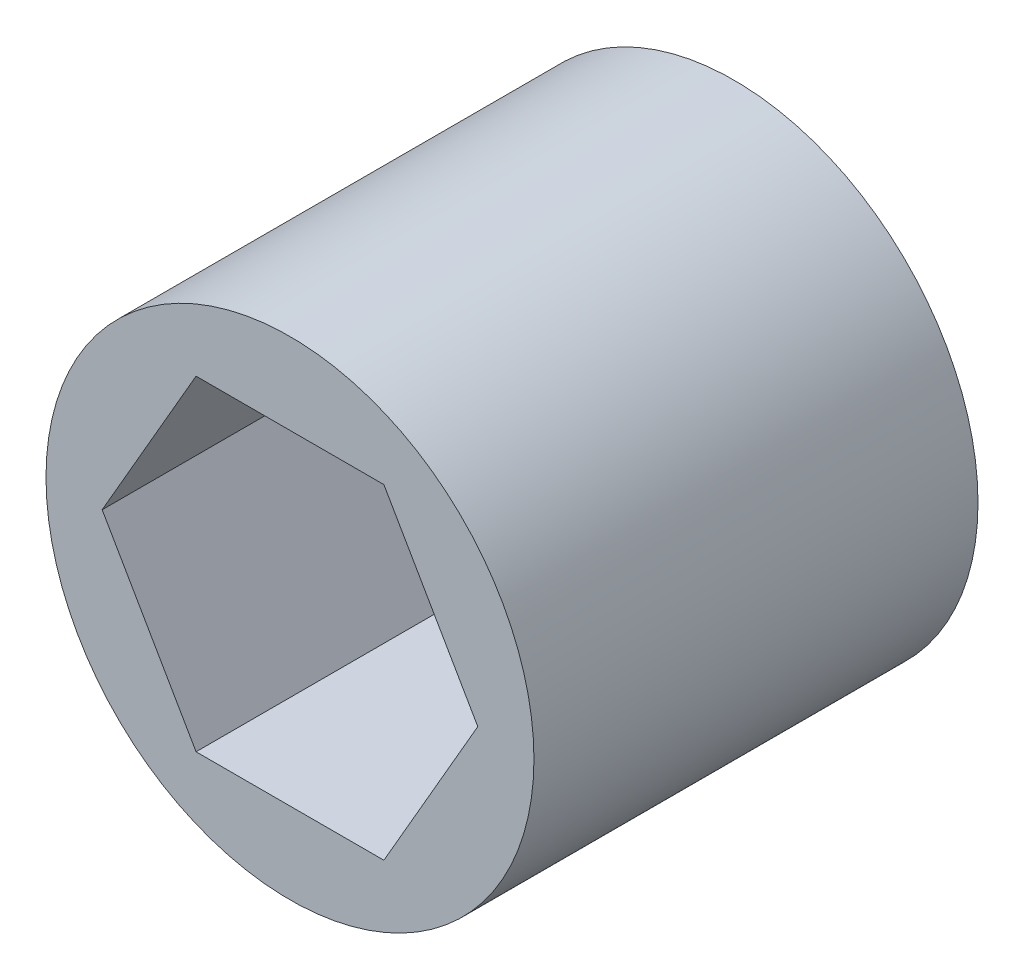
SolidWorks part; units mm, degrees
material "PET"
ref_plane "Front Plane" through (0, 0, 0) normal (0, 0, 1) x (1, 0, 0)
ref_plane "Top Plane" through (0, 0, 0) normal (0, 1, 0) x (1, 0, 0)
ref_plane "Right Plane" through (0, 0, 0) normal (1, 0, 0) x (0, 0, -1)
sketch "Sketch1" plane through (0, 0, 0) normal (0, 0, 1) x (1, 0, 0)
  line L1 (7.3323, 0) -> (3.6662, 6.35)
  line L2 (3.6662, 6.35) -> (-3.6662, 6.35)
  line L3 (-3.6662, 6.35) -> (-7.3323, 0)
  line L4 (-7.3323, 0) -> (-3.6662, -6.35)
  line L5 (-3.6662, -6.35) -> (3.6662, -6.35)
  line L6 (3.6662, -6.35) -> (7.3323, 0)
  circle A1 centre (0, 0) radius 6.35 construction
  circle A2 centre (0, 0) radius 9.525
  dimension "D1" = 12.7
  dimension "D2" = 19.05
extrude "Boss-Extrude1" add sketch "Sketch1" along normal blind 17.3355 contours L5 L6 L1 L2 L3 L4 | A2
